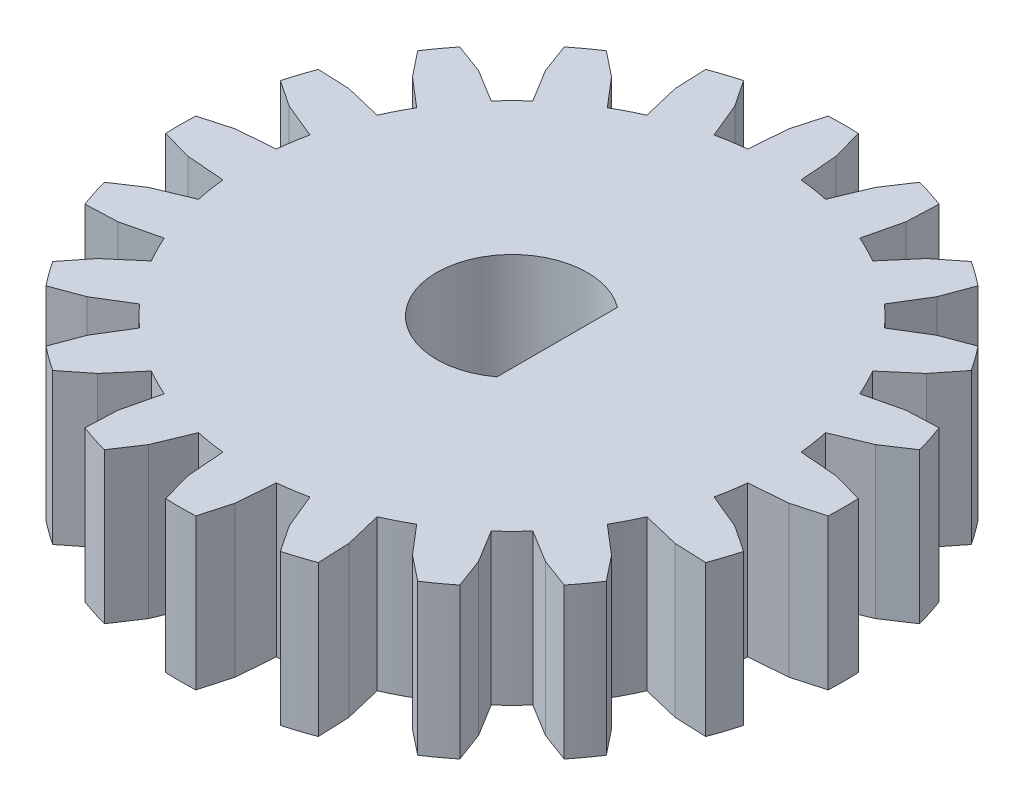
SolidWorks part; units mm, degrees
ref_plane "Front Plane" through (0, 0, 0) normal (0, 0, 1) x (1, 0, 0)
ref_plane "Top Plane" through (0, 0, 0) normal (0, 1, 0) x (1, 0, 0)
ref_plane "Right Plane" through (0, 0, 0) normal (1, 0, 0) x (0, 0, -1)
sketch "Sketch1" plane through (0, 0, 0) normal (0, 1, 0) x (1, 0, 0)
  line L0 (0, -21.5041) -> (0, 21.5041) construction
  line L1 (0.785, 9.9691) -> (0.5, 10.9886)
  line L2 (0.785, 9.9691) -> (0.885, 8.7051)
  line L3 (-0.785, 9.9691) -> (-0.885, 8.7051)
  line L4 (-0.785, 9.9691) -> (-0.5, 10.9886)
  line L5 (2.3341, 9.7238) -> (1.8483, 8.5525)
  line L6 (2.3341, 9.7238) -> (2.9201, 10.6053)
  line L7 (3.8272, 9.2386) -> (3.8712, 10.2963)
  line L8 (3.8272, 9.2386) -> (3.5317, 8.0056)
  line L9 (5.2246, 8.5266) -> (4.4008, 7.5628)
  line L10 (5.2246, 8.5266) -> (6.0544, 9.1839)
  line L11 (6.4948, 7.6038) -> (6.8635, 8.5961)
  line L12 (6.4948, 7.6038) -> (5.8327, 6.5224)
  line L13 (7.6038, 6.4948) -> (6.5224, 5.8327)
  line L14 (7.6038, 6.4948) -> (8.5961, 6.8635)
  line L15 (8.5266, 5.2246) -> (9.1839, 6.0544)
  line L16 (8.5266, 5.2246) -> (7.5628, 4.4008)
  line L17 (9.2386, 3.8272) -> (8.0056, 3.5317)
  line L18 (9.2386, 3.8272) -> (10.2963, 3.8712)
  line L19 (9.7238, 2.3341) -> (10.6053, 2.9201)
  line L20 (9.7238, 2.3341) -> (8.5525, 1.8483)
  line L21 (9.9691, 0.785) -> (8.7051, 0.885)
  line L22 (9.9691, 0.785) -> (10.9886, 0.5)
  line L23 (9.9691, -0.785) -> (10.9886, -0.5)
  line L24 (9.9691, -0.785) -> (8.7051, -0.885)
  line L25 (9.7238, -2.3341) -> (8.5525, -1.8483)
  line L26 (9.7238, -2.3341) -> (10.6053, -2.9201)
  line L27 (9.2386, -3.8272) -> (10.2963, -3.8712)
  line L28 (9.2386, -3.8272) -> (8.0056, -3.5317)
  line L29 (8.5266, -5.2246) -> (7.5628, -4.4008)
  line L30 (8.5266, -5.2246) -> (9.1839, -6.0544)
  line L31 (7.6038, -6.4948) -> (8.5961, -6.8635)
  line L32 (7.6038, -6.4948) -> (6.5224, -5.8327)
  line L33 (6.4948, -7.6038) -> (5.8327, -6.5224)
  line L34 (6.4948, -7.6038) -> (6.8635, -8.5961)
  line L35 (5.2246, -8.5266) -> (6.0544, -9.1839)
  line L36 (5.2246, -8.5266) -> (4.4008, -7.5628)
  line L37 (3.8272, -9.2386) -> (3.5317, -8.0056)
  line L38 (3.8272, -9.2386) -> (3.8712, -10.2963)
  line L39 (2.3341, -9.7238) -> (2.9201, -10.6053)
  line L40 (2.3341, -9.7238) -> (1.8483, -8.5525)
  line L41 (0.785, -9.9691) -> (0.885, -8.7051)
  line L42 (0.785, -9.9691) -> (0.5, -10.9886)
  line L43 (-0.785, -9.9691) -> (-0.5, -10.9886)
  line L44 (-0.785, -9.9691) -> (-0.885, -8.7051)
  line L45 (-2.3341, -9.7238) -> (-1.8483, -8.5525)
  line L46 (-2.3341, -9.7238) -> (-2.9201, -10.6053)
  line L47 (-3.8272, -9.2386) -> (-3.8712, -10.2963)
  line L48 (-3.8272, -9.2386) -> (-3.5317, -8.0056)
  line L49 (-5.2246, -8.5266) -> (-4.4008, -7.5628)
  line L50 (-5.2246, -8.5266) -> (-6.0544, -9.1839)
  line L51 (-6.4948, -7.6038) -> (-6.8635, -8.5961)
  line L52 (-6.4948, -7.6038) -> (-5.8327, -6.5224)
  line L53 (-7.6038, -6.4948) -> (-6.5224, -5.8327)
  line L54 (-7.6038, -6.4948) -> (-8.5961, -6.8635)
  line L55 (-8.5266, -5.2246) -> (-9.1839, -6.0544)
  line L56 (-8.5266, -5.2246) -> (-7.5628, -4.4008)
  line L57 (-9.2386, -3.8272) -> (-8.0056, -3.5317)
  line L58 (-9.2386, -3.8272) -> (-10.2963, -3.8712)
  line L59 (-9.7238, -2.3341) -> (-10.6053, -2.9201)
  line L60 (-9.7238, -2.3341) -> (-8.5525, -1.8483)
  line L61 (-9.9691, -0.785) -> (-8.7051, -0.885)
  line L62 (-9.9691, -0.785) -> (-10.9886, -0.5)
  line L63 (-9.9691, 0.785) -> (-10.9886, 0.5)
  line L64 (-9.9691, 0.785) -> (-8.7051, 0.885)
  line L65 (-9.7238, 2.3341) -> (-8.5525, 1.8483)
  line L66 (-9.7238, 2.3341) -> (-10.6053, 2.9201)
  line L67 (-9.2386, 3.8272) -> (-10.2963, 3.8712)
  line L68 (-9.2386, 3.8272) -> (-8.0056, 3.5317)
  line L69 (-8.5266, 5.2246) -> (-7.5628, 4.4008)
  line L70 (-8.5266, 5.2246) -> (-9.1839, 6.0544)
  line L71 (-7.6038, 6.4948) -> (-8.5961, 6.8635)
  line L72 (-7.6038, 6.4948) -> (-6.5224, 5.8327)
  line L73 (-6.4948, 7.6038) -> (-5.8327, 6.5224)
  line L74 (-6.4948, 7.6038) -> (-6.8635, 8.5961)
  line L75 (-5.2246, 8.5266) -> (-6.0544, 9.1839)
  line L76 (-5.2246, 8.5266) -> (-4.4008, 7.5628)
  line L77 (-3.8272, 9.2386) -> (-3.5317, 8.0056)
  line L78 (-3.8272, 9.2386) -> (-3.8712, 10.2963)
  line L79 (-2.3341, 9.7238) -> (-2.9201, 10.6053)
  line L80 (-2.3341, 9.7238) -> (-1.8483, 8.5525)
  line L81 (1.5, 2) -> (1.5, -2)
  circle A0 centre (0, 0) radius 10 construction
  circle A1 centre (0, 0) radius 8.75
  arc A2 (0.5, 10.9886) -> (-0.5, 10.9886) centre (0, 0) ccw
  arc A3 (3.8712, 10.2963) -> (2.9201, 10.6053) centre (0, 0) ccw
  arc A4 (6.8635, 8.5961) -> (6.0544, 9.1839) centre (0, 0) ccw
  arc A5 (9.1839, 6.0544) -> (8.5961, 6.8635) centre (0, 0) ccw
  arc A6 (10.6053, 2.9201) -> (10.2963, 3.8712) centre (0, 0) ccw
  arc A7 (10.9886, -0.5) -> (10.9886, 0.5) centre (0, 0) ccw
  arc A8 (10.2963, -3.8712) -> (10.6053, -2.9201) centre (0, 0) ccw
  arc A9 (8.5961, -6.8635) -> (9.1839, -6.0544) centre (0, 0) ccw
  arc A10 (6.0544, -9.1839) -> (6.8635, -8.5961) centre (0, 0) ccw
  arc A11 (2.9201, -10.6053) -> (3.8712, -10.2963) centre (0, 0) ccw
  arc A12 (-0.5, -10.9886) -> (0.5, -10.9886) centre (0, 0) ccw
  arc A13 (-3.8712, -10.2963) -> (-2.9201, -10.6053) centre (0, 0) ccw
  arc A14 (-6.8635, -8.5961) -> (-6.0544, -9.1839) centre (0, 0) ccw
  arc A15 (-9.1839, -6.0544) -> (-8.5961, -6.8635) centre (0, 0) ccw
  arc A16 (-10.6053, -2.9201) -> (-10.2963, -3.8712) centre (0, 0) ccw
  arc A17 (-10.9886, 0.5) -> (-10.9886, -0.5) centre (0, 0) ccw
  arc A18 (-10.2963, 3.8712) -> (-10.6053, 2.9201) centre (0, 0) ccw
  arc A19 (-8.5961, 6.8635) -> (-9.1839, 6.0544) centre (0, 0) ccw
  arc A20 (-6.0544, 9.1839) -> (-6.8635, 8.5961) centre (0, 0) ccw
  arc A21 (-2.9201, 10.6053) -> (-3.8712, 10.2963) centre (0, 0) ccw
  arc A22 (1.5, 2) -> (1.5, -2) centre (0, 0) ccw
  point P5 (0.785, 9.9691)
  point P8 (0, 0)
  point P15 (-0.785, 9.9691)
  point P132 (0, 0)
  dimension "D1" = 20
  dimension "D2" = 22
  dimension "D3" = 17.5
  dimension "D7" = 20
  dimension "D8" = 5
  dimension "D4" = 0.785
  dimension "D5" = 0.885
  dimension "D6" = 0.5
  dimension "D9" = 4
extrude "Boss-Extrude1" add sketch "Sketch1" along normal blind 5 contours A1 | L71 A19 L70 L69 A1 L72 | L75 A20 L74 L73 A1 L76 | L7 A3 L6 L5 A1 L8 | L11 A4 L10 L9 A1 L12 | L15 A5 L14 L13 A1 L16 | L19 A6 L18 L17 A1 L20 | L23 A7 L22 L21 A1 L24 | L27 A8 L26 L25 A1 L28 | L31 A9 L30 L29 A1 L32 | L35 A10 L34 L33 A1 L36 | L39 A11 L38 L37 A1 L40 | L43 A12 L42 L41 A1 L44 | L47 A13 L46 L45 A1 L48 | L51 A14 L50 L49 A1 L52 | L55 A15 L54 L53 A1 L56 | L59 A16 L58 L57 A1 L60 | L63 A17 L62 L61 A1 L64 | L67 A18 L66 L65 A1 L68 | L1 A2 L4 L3 A1 L2 | L79 A21 L78 L77 A1 L80
sketch "Sketch2" plane through (0, 0, 0) normal (1, 0, 0) x (0, 0, -1)
  line L0 (0, -12.8905) -> (0, 12.8905) construction
  point P3 (0, 0)
